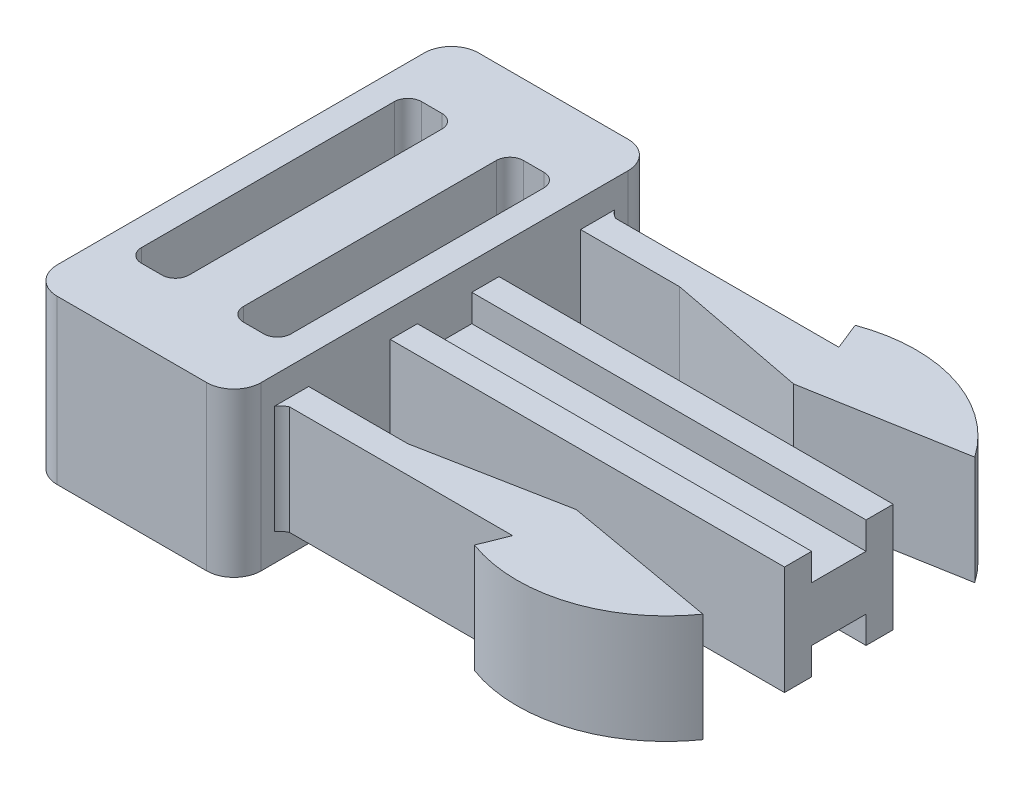
SolidWorks part; units mm, degrees
ref_plane "Front Plane" through (0, 0, 0) normal (0, 0, 1) x (1, 0, 0)
ref_plane "Top Plane" through (0, 0, 0) normal (0, 1, 0) x (1, 0, 0)
ref_plane "Right Plane" through (0, 0, 0) normal (1, 0, 0) x (0, 0, -1)
sketch "Sketch1" plane through (0, 0, 0) normal (0, 1, 0) x (1, 0, 0)
  line L0 (19.05, 36.83) -> (19.05, 2.54)
  line L1 (2.54, 0) -> (16.51, 0)
  line L2 (0, 2.54) -> (0, 36.83)
  line L3 (2.54, 39.37) -> (16.51, 39.37)
  arc A0 (19.05, 2.54) -> (16.51, 0) centre (16.51, 2.54) cw
  arc A1 (2.54, 0) -> (0, 2.54) centre (2.54, 2.54) cw
  arc A2 (0, 36.83) -> (2.54, 39.37) centre (2.54, 36.83) cw
  arc A3 (16.51, 39.37) -> (19.05, 36.83) centre (16.51, 36.83) cw
  point P9 (0, 0)
  point P12 (0, 39.37)
  point P15 (19.05, 39.37)
  dimension "D3" = 2.54
  dimension "D1" = 39.37
  dimension "D2" = 19.05
extrude "Boss-Extrude1" add sketch "Sketch1" along normal blind 15.24
sketch "Sketch3" plane through (0, 15.24, 0) normal (0, 1, 0) x (1, 0, 0)
  line L0 (9.525, 39.37) -> (9.525, 0) construction
  line L1 (16.51, 39.37) -> (2.54, 39.37) construction
  line L2 (2.54, 0) -> (16.51, 0) construction
  line L3 (6.985, 31.496) -> (6.985, 7.874)
  line L4 (12.065, 31.496) -> (12.065, 7.874)
  line L5 (0, 19.685) -> (19.05, 19.685) construction
  line L6 (0, 36.83) -> (0, 2.54) construction
  line L7 (19.05, 2.54) -> (19.05, 36.83) construction
  line L8 (3.81, 6.604) -> (5.715, 6.604)
  line L9 (3.81, 32.766) -> (5.715, 32.766)
  line L12 (2.54, 36.83) -> (2.54, 2.54)
  line L13 (2.54, 31.496) -> (2.54, 7.874)
  line L14 (0, 32.766) -> (19.05, 32.766) construction
  line L15 (16.51, 2.54) -> (16.51, 36.83)
  line L16 (16.51, 7.874) -> (16.51, 31.496)
  line L17 (6.985, 39.37) -> (6.985, 0) construction
  line L18 (13.335, 32.766) -> (15.24, 32.766)
  line L19 (12.065, 39.37) -> (12.065, 0) construction
  line L20 (0, 6.604) -> (19.05, 6.604) construction
  line L21 (13.335, 6.604) -> (15.24, 6.604)
  arc A0 (13.335, 32.766) -> (12.065, 31.496) centre (13.335, 31.496) ccw
  arc A1 (15.24, 32.766) -> (16.51, 31.496) centre (15.24, 31.496) cw
  arc A2 (16.51, 7.874) -> (15.24, 6.604) centre (15.24, 7.874) cw
  arc A3 (13.335, 6.604) -> (12.065, 7.874) centre (13.335, 7.874) cw
  arc A4 (2.54, 7.874) -> (3.81, 6.604) centre (3.81, 7.874) ccw
  arc A5 (5.715, 6.604) -> (6.985, 7.874) centre (5.715, 7.874) ccw
  arc A6 (6.985, 31.496) -> (5.715, 32.766) centre (5.715, 31.496) ccw
  arc A7 (3.81, 32.766) -> (2.54, 31.496) centre (3.81, 31.496) ccw
  point P40 (12.065, 6.604)
  dimension "D7" = 1.27
  dimension "D1" = 2.54
  dimension "D2" = 2.54
  dimension "D3" = 13.081
  dimension "D4" = 13.081
  dimension "D5" = 2.54
  dimension "D6" = 2.54
extrude "Cut-Extrude1" cut sketch "Sketch3" against normal through all
ref_plane "Plane1" through (0, 2.54, 0) normal (0, 1, 0) x (1, 0, 0)
sketch "Sketch5" plane through (0, 2.54, 0) normal (0, 1, 0) x (1, 0, 0)
  line L1 (19.05, 2.54) -> (19.05, 36.83) construction
  line L5 (19.7952, 34.925) -> (40.64, 34.925)
  line L7 (19.3386, 32.385) -> (28.3028, 32.385)
  line L9 (19.05, 19.685) -> (71.4909, 19.685) construction
  line L10 (16.51, 39.37) -> (2.54, 39.37) construction
  line L11 (41.5016, 29.845) -> (55.88, 32.385)
  line L12 (19.7952, 34.925) -> (55.88, 34.925) construction
  line L13 (19.3386, 32.385) -> (55.88, 32.385) construction
  line L14 (19.3386, 32.385) -> (19.05, 32.385)
  line L15 (19.05, 32.385) -> (19.05, 35.56)
  line L18 (41.5016, 29.845) -> (28.3028, 32.385)
  line L24 (19.05, 14.605) -> (55.88, 14.605)
  line L25 (19.05, 24.765) -> (55.88, 24.765)
  line L26 (55.88, 24.765) -> (55.88, 14.605)
  line L27 (19.05, 14.605) -> (71.4909, 14.605) construction
  line L28 (19.05, 24.765) -> (71.4909, 24.765) construction
  line L29 (19.05, 14.605) -> (19.05, 24.765)
  line L30 (40.64, 34.925) -> (39.624, 37.465)
  line L31 (19.7952, 4.445) -> (40.64, 4.445)
  line L32 (19.05, 6.985) -> (19.05, 3.81)
  line L33 (19.3386, 6.985) -> (19.05, 6.985)
  line L34 (19.3386, 6.985) -> (28.3028, 6.985)
  line L35 (41.5016, 9.525) -> (28.3028, 6.985)
  line L36 (41.5016, 9.525) -> (55.88, 6.985)
  line L37 (40.64, 4.445) -> (39.624, 1.905)
  arc A0 (19.05, 35.56) -> (19.7952, 34.925) centre (20.6344, 36.6646) ccw
  arc A1 (39.624, 37.465) -> (55.88, 32.385) centre (44.4596, 24.3894) cw
  arc A3 (16.9664, 34.1074) -> (19.3386, 32.385) centre (20.6344, 36.6646) ccw construction
  arc A5 (19.05, 3.81) -> (19.7952, 4.445) centre (20.6344, 2.7054) cw
  arc A6 (39.624, 1.905) -> (55.88, 6.985) centre (44.4596, 14.9806) ccw
  dimension "D1" = 3.81
  dimension "D2" = 36.83
  dimension "D4" = 2.54
  dimension "D5" = 2.54
  dimension "D6" = 21.59
  dimension "D9" = 36.83
  dimension "D11" = 16.256
  dimension "D3" = 2.54
  dimension "D7" = 5.08
  dimension "D8" = 5.08
extrude "Boss-Extrude2" add sketch "Sketch5" along normal blind 10.16
sketch "Sketch7" plane through (0, 12.7, 0) normal (0, 1, 0) x (1, 0, 0)
  line L0 (55.88, 19.685) -> (19.05, 19.685) construction
  line L1 (55.88, 14.605) -> (55.88, 24.765) construction
  line L2 (19.05, 2.54) -> (19.05, 36.83) construction
  line L3 (55.88, 22.225) -> (19.05, 22.225)
  line L4 (55.88, 17.145) -> (19.05, 17.145)
  line L5 (19.05, 17.145) -> (19.05, 22.225)
  line L6 (55.88, 17.145) -> (55.88, 22.225)
  dimension "D1" = 2.54
  dimension "D2" = 2.54
extrude "Cut-Extrude2" cut sketch "Sketch7" against normal blind 2.54
ref_plane "Plane2" through (0, 7.62, 0) normal (0, 1, 0) x (1, 0, 0)
mirror "Mirror1" about plane through (0, 7.62, 0) normal (0, 1, 0) of "Cut-Extrude2"
